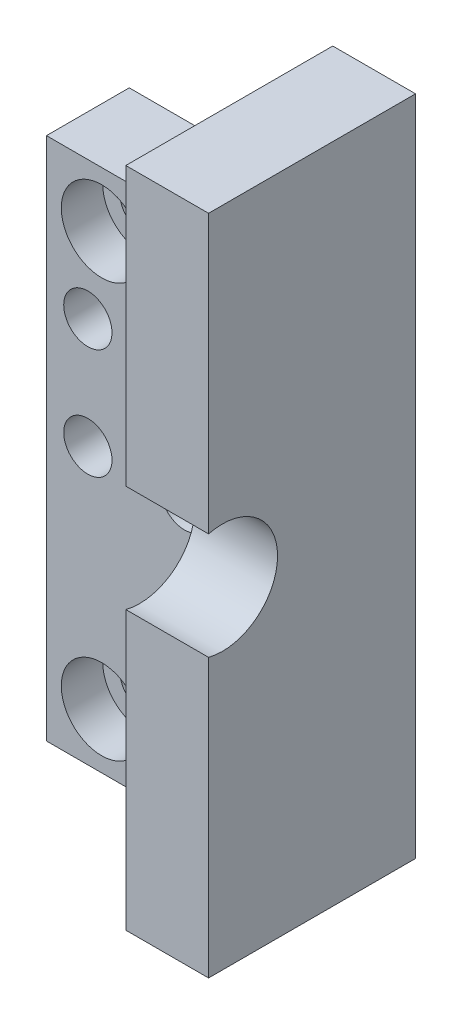
SolidWorks part; units mm, degrees
ref_plane "Front Plane" through (0, 0, 0) normal (0, 0, 1) x (1, 0, 0)
ref_plane "Top Plane" through (0, 0, 0) normal (0, 1, 0) x (1, 0, 0)
ref_plane "Right Plane" through (0, 0, 0) normal (1, 0, 0) x (0, 0, -1)
sketch "Sketch1" plane through (0, 0, 0) normal (0, 0, 1) x (1, 0, 0)
  line L0 (16.75, 48) -> (16.75, 0) construction
  line L1 (0, 0) -> (20.75, 0)
  line L2 (0, 0) -> (0, 48)
  line L3 (0, 48) -> (20.75, 48)
  line L4 (20.75, 0) -> (20.75, 48)
  circle A0 centre (16.75, 34) radius 1.675
  circle A1 centre (16.75, 4) radius 1.675
  dimension "D2" = 3.35
  dimension "D3" = 3.35
  dimension "D1" = 16.75
  dimension "D4" = 30
  dimension "D5" = 14
  dimension "D6" = 4
  dimension "D7" = 4
extrude "Boss-Extrude1" add sketch "Sketch1" along normal blind 6
sketch "Sketch2" plane through (0, 0, 0) normal (-1, 0, 0) x (0, 0, 1)
  line L1 (0, 48) -> (15, 48)
  line L2 (0, 48) -> (0, 0)
  line L3 (0, 0) -> (15, 0)
  line L4 (15, 48) -> (15, 0)
  dimension "D1" = 15
extrude "Boss-Extrude2" add sketch "Sketch2" against normal blind 6
sketch "Sketch3" plane through (0, 0, 0) normal (-1, 0, 0) x (0, 0, 1)
  line L0 (14, 48) -> (14, 0) construction
  line L1 (15, 48) -> (0, 48) construction
  line L2 (15, 0) -> (0, 0) construction
  line L3 (14, 24) -> (14.0919, 24) construction
  line L4 (0, 48) -> (0, 0) construction
  circle A0 centre (14, 24) radius 4
  point P10 (18, 23.7731)
  dimension "D1" = 8
  dimension "D3" = 14
extrude "Cut-Extrude1" cut sketch "Sketch3" against normal blind 6
sketch "Sketch5" plane through (0, 0, 6) normal (0, 0, 1) x (1, 0, 0)
  circle A0 centre (16.75, 34) radius 2.925
  circle A1 centre (16.75, 4) radius 2.925
  dimension "D1" = 5.85
  dimension "D2" = 5.85
extrude "Cut-Extrude2" cut sketch "Sketch5" against normal blind 3
sketch "Sketch6" plane through (0, 0, 6) normal (0, 0, 1) x (1, 0, 0)
  line L0 (20.75, 24) -> (8.4532, 24) construction
  line L1 (20.75, 0) -> (20.75, 48) construction
  circle A0 centre (10.75, 28) radius 1.75
  circle A1 centre (17.75, 28) radius 1.75
  circle A2 centre (10.75, 20) radius 1.75
  circle A3 centre (17.75, 20) radius 1.75
  dimension "D1" = 4
  dimension "D3" = 3.5
  dimension "D4" = 3.5
  dimension "D2" = 4
  dimension "D5" = 7
  dimension "D6" = 3
extrude "Cut-Extrude3" cut sketch "Sketch6" against normal blind 10
sketch "Sketch7" plane through (0, 0, 0) normal (0, 0, -1) x (-1, 0, 0)
  line L1 (-19.5, 28) -> (-16, 28)
  line L2 (-19.5, 28) -> (-19.5, 20)
  line L3 (-19.5, 20) -> (-16, 20)
  line L4 (-16, 28) -> (-16, 20)
  line L5 (-12.5, 20) -> (-9, 20)
  line L6 (-12.5, 20) -> (-12.5, 28)
  line L7 (-12.5, 28) -> (-9, 28)
  line L8 (-9, 20) -> (-9, 28)
  circle A0 centre (-17.75, 28) radius 1.75 construction
  circle A1 centre (-17.75, 20) radius 1.75 construction
  circle A2 centre (-10.75, 20) radius 1.75 construction
  circle A3 centre (-10.75, 28) radius 1.75 construction
extrude "Cut-Extrude4" cut sketch "Sketch7" against normal blind 2.5
sketch "Sketch8" plane through (0, 0, 6) normal (0, 0, 1) x (1, 0, 0)
  line L0 (20.75, 38) -> (6, 38)
  line L1 (20.75, 0) -> (20.75, 48) construction
  line L2 (6, 0) -> (6, 48) construction
  line L3 (6, 38) -> (6, 48)
  line L4 (6, 48) -> (20.75, 48)
  line L5 (20.75, 48) -> (20.75, 38)
  point P9 (6, 48)
  dimension "D1" = 10
extrude "Cut-Extrude5" cut sketch "Sketch8" against normal blind 16
sketch3d "3DSketch3"
  point P0 (20.75, 10.9724, 2.2496)
mirror "Mirror3" about plane through (20.75, 0, 6) normal (-1, 0, 0) of "Boss-Extrude1", "Boss-Extrude2", "Cut-Extrude1", "Cut-Extrude2", "Cut-Extrude3", "Cut-Extrude4", "Cut-Extrude5"
sketch "Sketch9" plane through (0, 0, 0) normal (-1, 0, 0) x (0, 0, 1)
  line L1 (15, 48) -> (0, 48)
  line L2 (15, 48) -> (15, 0)
  line L3 (15, 0) -> (0, 0)
  line L4 (0, 48) -> (0, 0)
extrude "Cut-Extrude6" cut sketch "Sketch9" against normal blind 20.75
